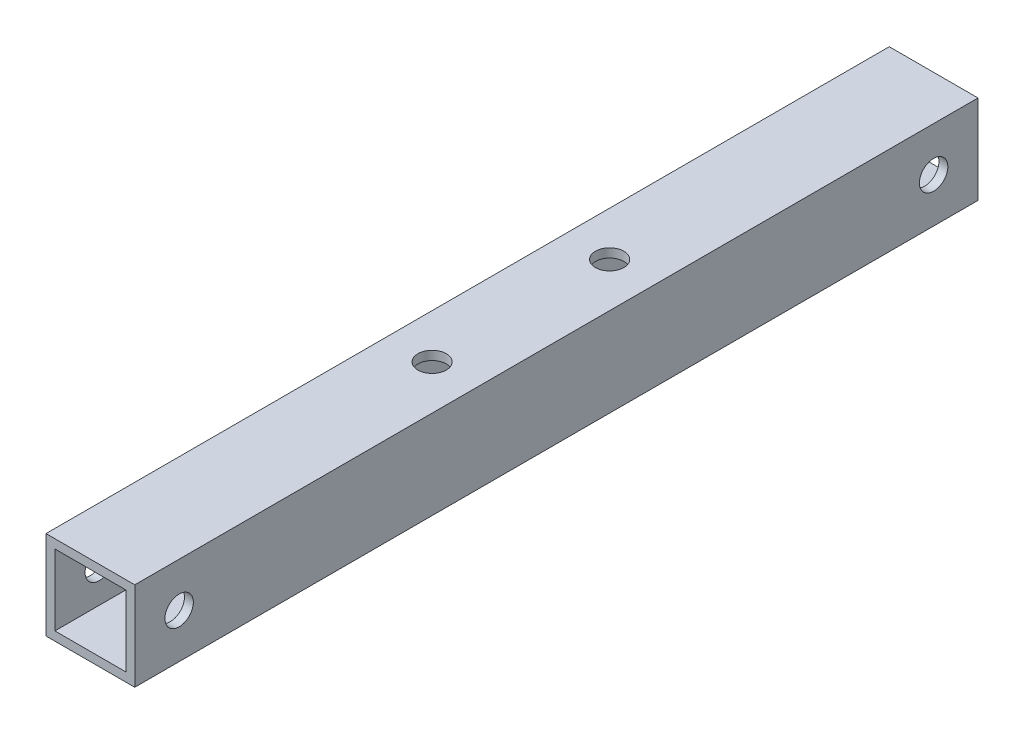
SolidWorks part; units mm, degrees
material "5052-H34"
ref_plane "正面" through (0, 0, 0) normal (0, 0, 1) x (1, 0, 0)
ref_plane "平面" through (0, 0, 0) normal (0, 1, 0) x (1, 0, 0)
ref_plane "右側面" through (0, 0, 0) normal (1, 0, 0) x (0, 0, -1)
sketch "ｽｹｯﾁ1" plane through (0, 0, 0) normal (0, 0, 1) x (1, 0, 0)
  line L1 (5, 5) -> (-5, 5)
  line L2 (5, 5) -> (5, -5)
  line L3 (5, -5) -> (-5, -5)
  line L4 (-5, 5) -> (-5, -5)
  line L5 (5, 5) -> (-5, -5) construction
  line L6 (5, -5) -> (-5, 5) construction
  point P0 (0, 0)
  dimension "D1" = 10
extrude "押し出し-薄板1" add sketch "ｽｹｯﾁ1" along normal blind 95 thin thin type one direction reverse wall 1
sketch "ｽｹｯﾁ3" plane through (0, 5, 0) normal (0, 1, 0) x (1, 0, 0)
  line L0 (0, 0) -> (0, -95) construction
  line L1 (5, 0) -> (-5, 0) construction
  line L2 (5, -95) -> (-5, -95) construction
  line L3 (0, -47.5) -> (5, -47.5) construction
  line L4 (5, -95) -> (5, 0) construction
  circle A0 centre (0, -56.5) radius 1.6
  circle A1 centre (0, -36.5) radius 1.6
  dimension "D1" = 3.2
  dimension "D3" = 20
  dimension "D4" = 3.2
  dimension "D2" = 11
extrude "ｶｯﾄ - 押し出し2" cut sketch "ｽｹｯﾁ3" against normal through all
sketch "ｽｹｯﾁ4" plane through (5, 0, 0) normal (1, 0, 0) x (0, 0, -1)
  line L0 (-95, 0) -> (0, 0) construction
  line L1 (-95, -5) -> (-95, 5) construction
  line L2 (-47.5, 0) -> (-47.5, 5) construction
  line L3 (-95, 5) -> (0, 5) construction
  circle A0 centre (-90, 0) radius 1.6
  circle A1 centre (-5, 0) radius 1.6
  dimension "D1" = 5
  dimension "D2" = 3.2
extrude "ｶｯﾄ - 押し出し3" cut sketch "ｽｹｯﾁ4" against normal through all
